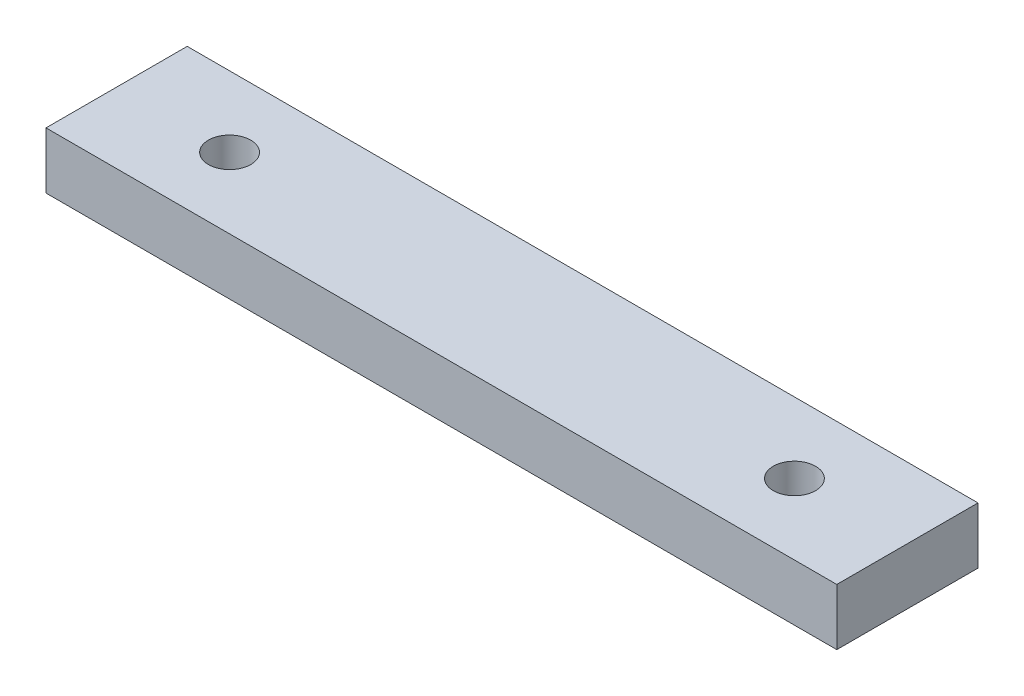
SolidWorks part; units mm, degrees
ref_plane "Front Plane" through (0, 0, 0) normal (0, 0, 1) x (1, 0, 0)
ref_plane "Top Plane" through (0, 0, 0) normal (0, 1, 0) x (1, 0, 0)
ref_plane "Right Plane" through (0, 0, 0) normal (1, 0, 0) x (0, 0, -1)
sketch "Sketch1" plane through (0, 0, 0) normal (0, 1, 0) x (1, 0, 0)
  line L0 (-28, -3.9105) -> (82, -3.9105) construction
  line L2 (-28, -8.9105) -> (-28, 1.0895)
  line L3 (-4.75, 21.0895) -> (4.75, 21.0895)
  line L4 (28, -8.9105) -> (28, 1.0895)
  line L7 (-4.75, -28.9105) -> (4.75, -28.9105)
  line L9 (-4.75, 21.0895) -> (4.75, 21.0895)
  line L11 (-4.75, -28.9105) -> (-4.75, -8.9105)
  line L12 (-4.75, -8.9105) -> (-28, -8.9105)
  line L13 (-28, 1.0895) -> (-4.75, 1.0895)
  line L14 (-4.75, 1.0895) -> (-4.75, 21.0895)
  line L15 (4.75, 21.0895) -> (4.75, 1.0895)
  line L16 (4.75, 1.0895) -> (28, 1.0895)
  line L17 (4.75, -28.9105) -> (4.75, -8.9105)
  line L18 (4.75, -8.9105) -> (28, -8.9105)
  line L19 (4.75, 1.0895) -> (-4.75, 1.0895)
  line L20 (-4.75, -8.9105) -> (4.75, -8.9105)
  line L21 (4.75, -8.9105) -> (4.75, 1.0895) construction
  line L22 (-4.75, 1.0895) -> (-4.75, -8.9105) construction
  line L23 (0, 21.0895) -> (0, -28.9105) construction
  circle A0 centre (-20, -3.9105) radius 1.5
  circle A1 centre (20, -3.9105) radius 1.5
  point P0 (0, 0)
  point P1 (0, 0)
  point P6 (-1.5869, 0.6545)
  point P27 (0, 0)
  point P28 (0, 0)
  dimension "D2" = 3
  dimension "D4" = 3
  dimension "D5" = 8
  dimension "D6" = 8
  dimension "D7" = 9.5
  dimension "D8" = 10
  dimension "D9" = 25
  dimension "D10" = 20
  dimension "D11" = 20
extrude "Boss-Extrude1" add sketch "Sketch1" along normal blind 4
